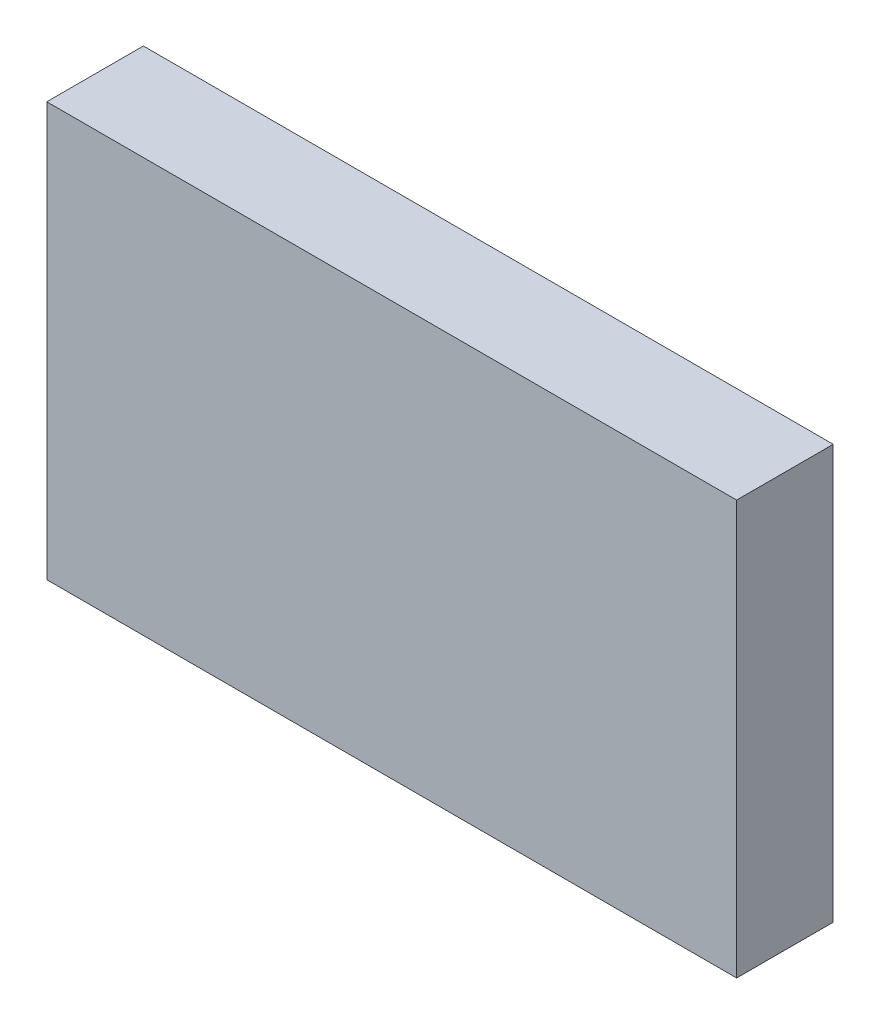
SolidWorks part; units mm, degrees
ref_plane "Plan de face" through (0, 0, 0) normal (0, 0, 1) x (1, 0, 0)
ref_plane "Plan de dessus" through (0, 0, 0) normal (0, 1, 0) x (1, 0, 0)
ref_plane "Plan de droite" through (0, 0, 0) normal (1, 0, 0) x (0, 0, -1)
sketch "Esquisse1" plane through (0, 0, 0) normal (0, 0, 1) x (1, 0, 0)
  line L1 (-25, 15) -> (25, 15)
  line L2 (-25, 15) -> (-25, -15)
  line L3 (-25, -15) -> (25, -15)
  line L4 (25, 15) -> (25, -15)
  line L5 (-25, 15) -> (25, -15) construction
  line L6 (-25, -15) -> (25, 15) construction
  point P0 (0, 0)
  dimension "D1" = 50
  dimension "D2" = 30
extrude "Boss.-Extru.1" add sketch "Esquisse1" along normal mid plane 7
